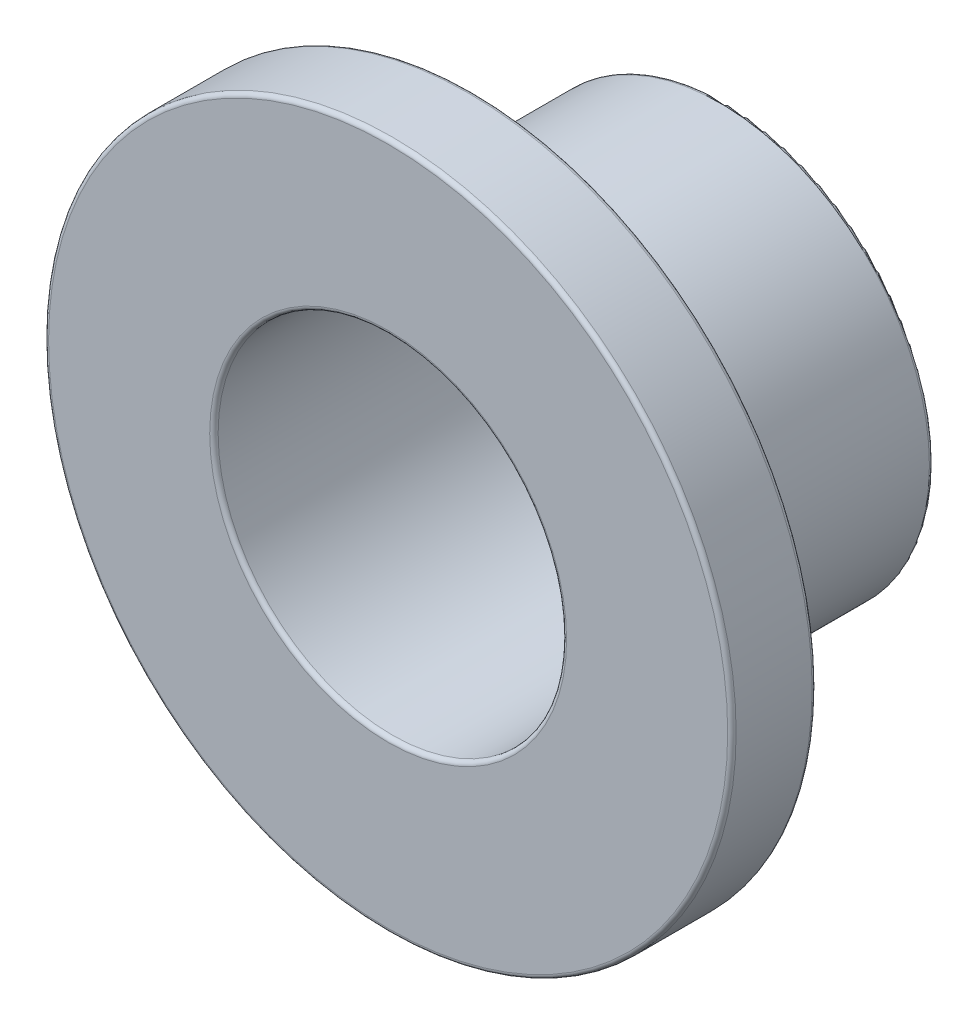
SolidWorks part; units mm, degrees
ref_plane "Front Plane" through (0, 0, 0) normal (0, 0, 1) x (1, 0, 0)
ref_plane "Top Plane" through (0, 0, 0) normal (0, 1, 0) x (1, 0, 0)
ref_plane "Right Plane" through (0, 0, 0) normal (1, 0, 0) x (0, 0, -1)
sketch "Sketch1" plane through (0, 0, 0) normal (-1, 0, 0) x (0, 0, 1)
  line L0 (3.1877, 3.302) -> (-3.1877, 3.302)
  line L1 (-3.1877, 3.302) -> (-3.1877, 3.9624)
  line L2 (-3.1877, 3.9624) -> (1.5875, 3.9624)
  line L3 (1.5875, 3.9624) -> (1.5875, 6.5151)
  line L4 (1.5875, 6.5151) -> (3.1877, 6.5151)
  line L6 (3.1877, 6.5151) -> (3.1877, 3.302)
  line L7 (3.1877, 0) -> (-3.1877, 0) construction
  dimension "ID" = 6.604
  dimension "OD" = 13.0302
  dimension "Sleeve OD" = 7.9248
  dimension "Thickness" = 1.6002
  dimension "Overall Height" = 6.3754
sketch "Sketch2" plane through (0, 0, 0) normal (1, 0, 0) x (0, 0, -1)
  line L6 (-3.1877, 3.302) -> (3.1877, 3.302)
  line L7 (3.1877, 3.302) -> (3.1877, 3.9624)
  line L8 (3.1877, 3.9624) -> (-1.5875, 3.9624)
  line L9 (-1.5875, 3.9624) -> (-1.5875, 6.5151)
  line L10 (-1.5875, 6.5151) -> (-3.1877, 6.5151)
  line L11 (-3.1877, 6.5151) -> (-3.1877, 3.302)
  line L12 (-3.1877, 3.302) -> (3.1877, 3.302)
  line L13 (3.1877, 3.302) -> (3.1877, 3.9624)
  line L14 (3.1877, 3.9624) -> (-1.5875, 3.9624)
  line L15 (-1.5875, 3.9624) -> (-1.5875, 6.5151)
  line L16 (-1.5875, 6.5151) -> (-3.1877, 6.5151)
  line L17 (-3.1877, 6.5151) -> (-3.1877, 3.302)
  dimension "D1" = 0
revolve "Revolve1" add sketch "Sketch2" angle 360 about L7
fillet "Fillet1" radius 0.08 6 edges at (3.302, 0, 3.1877) (3.302, 0, -3.1877) (3.9624, 0, -3.1877) (3.9624, 0, 1.5875) (6.5151, 0, 1.5875) (6.5151, 0, 3.1877)
equation "\"D1@Fillet1\"=\"Thickness@Sketch1\"*0.05"
